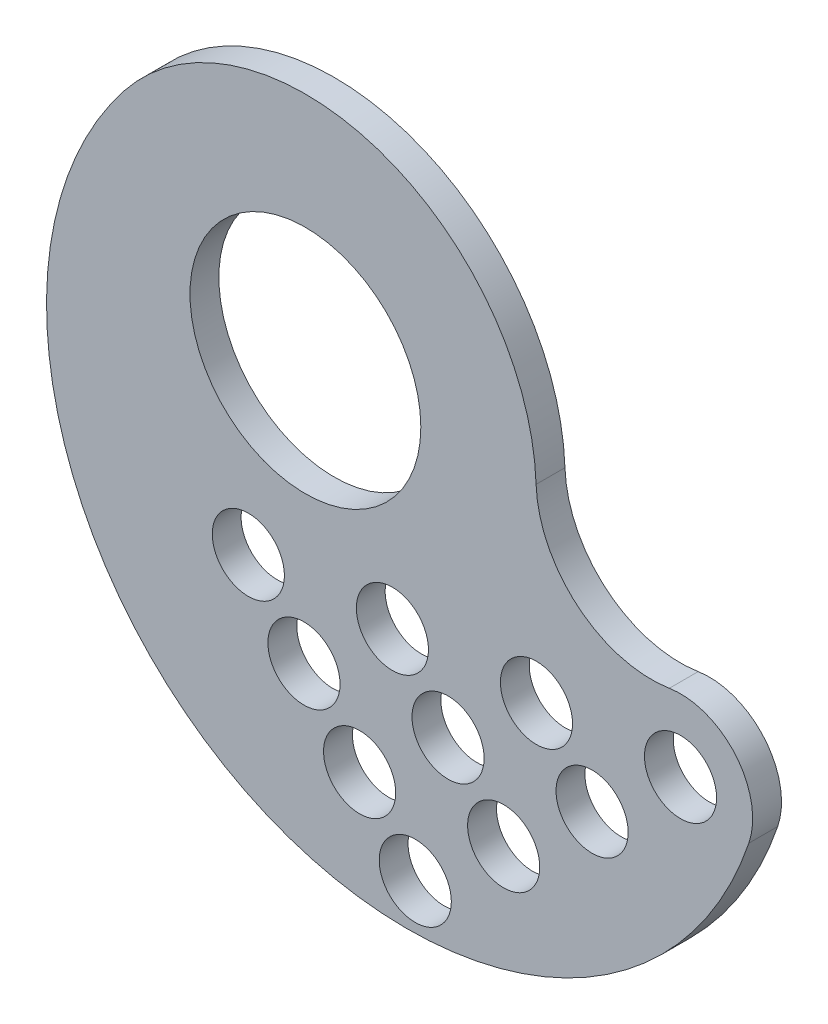
SolidWorks part; units mm, degrees
ref_plane "Alzado" through (0, 0, 0) normal (0, 0, 1) x (1, 0, 0)
ref_plane "Planta" through (0, 0, 0) normal (0, 1, 0) x (1, 0, 0)
ref_plane "Vista lateral" through (0, 0, 0) normal (1, 0, 0) x (0, 0, -1)
sketch "Croquis1" plane through (0, 0, 0) normal (0, 0, 1) x (1, 0, 0)
  line L0 (38.0747, -137.1345) -> (99.3582, -85.7115) construction
  line L1 (38.0747, -137.1345) -> (-0.4926, -91.1718) construction
  arc A0 (79.9506, 2.8097) -> (-62.7215, 49.659) centre (0, 0) ccw
  arc A1 (153.6798, -68.0167) -> (126.1254, -35.3021) centre (130, -60) ccw
  arc A2 (79.9506, 2.8097) -> (126.1254, -35.3021) centre (119.926, 4.2146) ccw
  arc A3 (-62.7215, 49.659) -> (153.6798, -68.0167) centre (35.2808, -27.9332) ccw
  circle A4 centre (0, 0) radius 40
  circle A5 centre (130, -60) radius 12.5
  circle A6 centre (99.3582, -85.7115) radius 12.5
  circle A7 centre (68.7164, -111.423) radius 12.5
  circle A8 centre (38.0747, -137.1345) radius 12.5
  circle A9 centre (80.0746, -62.7302) radius 12.5
  circle A10 centre (49.4328, -88.4417) radius 12.5
  circle A11 centre (18.791, -114.1532) radius 12.5
  circle A12 centre (60.791, -39.7488) radius 12.5 [skipped]
  circle A13 centre (30.1492, -65.4603) radius 12.5
  circle A14 centre (-0.4926, -91.1718) radius 12.5
  circle A15 centre (41.5073, -16.7675) radius 12.5 [skipped]
  circle A16 centre (10.8656, -42.479) radius 12.5 [skipped]
  circle A17 centre (-19.7762, -68.1905) radius 12.5
  circle A18 centre (110.7164, -37.0187) radius 12.5 [skipped]
  circle A19 centre (91.4327, -14.0373) radius 12.5 [skipped]
  circle A20 centre (72.1491, 8.944) radius 12.5 [skipped]
  dimension "D1" = 80
  dimension "D2" = 25
  dimension "D3" = 40
  dimension "D4" = 125
  dimension "D7" = 80
  dimension "D8" = 25
  dimension "D5" = 130
  dimension "D6" = 60
  dimension "D11" = 30
  dimension "D12" = 40
  dimension "D9" = 4
  dimension "D10" = 4
extrude "Saliente-Extruir1" add sketch "Croquis1" along normal blind 10
